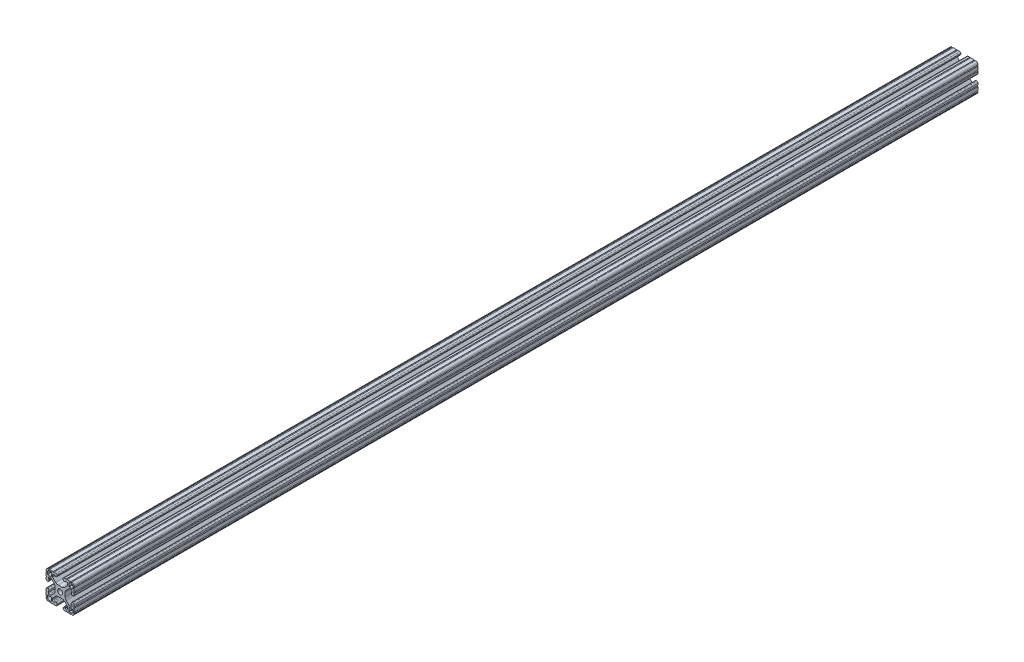
SolidWorks part; units mm, degrees
ref_plane "Front Plane" through (0, 0, 0) normal (0, 0, 1) x (1, 0, 0)
ref_plane "Top Plane" through (0, 0, 0) normal (0, 1, 0) x (1, 0, 0)
ref_plane "Right Plane" through (0, 0, 0) normal (1, 0, 0) x (0, 0, -1)
sketch "Sketch1" plane through (0, 0, 0) normal (0, 0, 1) x (1, 0, 0)
  line L0 (-10.0267, 12.1519) -> (-6.0215, 8.1473)
  line L1 (10.0267, -12.1519) -> (6.0215, -8.1473)
  line L2 (10.287, -14.5547) -> (10.287, -12.7802)
  line L3 (6.8141, -15.8247) -> (9.017, -15.8247)
  line L4 (-10.287, 14.5547) -> (-10.287, 12.7802)
  line L5 (6.8141, -14.986) -> (6.8141, -15.8247)
  line L6 (-6.8141, 15.8247) -> (-9.017, 15.8247)
  line L7 (2.6631, 6.7564) -> (-2.6631, 6.7564)
  line L8 (-6.8141, 14.986) -> (-6.8141, 15.8247)
  line L9 (-5.6388, 14.986) -> (-6.8141, 14.986)
  line L10 (-4.064, 17.4752) -> (-4.064, 16.5608)
  line L11 (-7.9756, 19.05) -> (-5.6388, 19.05)
  line L12 (-14.3256, 19.05) -> (-9.4996, 19.05)
  line L13 (-15.875, 19.05) -> (-15.8496, 19.05)
  line L14 (-19.05, 15.8496) -> (-19.05, 15.875)
  line L15 (-19.05, 9.4996) -> (-19.05, 14.3256)
  line L16 (-19.05, 5.6388) -> (-19.05, 7.9756)
  line L17 (5.6388, -14.986) -> (6.8141, -14.986)
  line L18 (4.064, -17.4752) -> (4.064, -16.5608)
  line L19 (7.9756, -19.05) -> (5.6388, -19.05)
  line L20 (-16.5608, 4.064) -> (-17.4752, 4.064)
  line L21 (14.3256, -19.05) -> (9.4996, -19.05)
  line L22 (-14.986, 6.7506) -> (-14.986, 5.6388)
  line L23 (-15.879, 6.7506) -> (-14.986, 6.7506)
  line L24 (15.875, -19.05) -> (15.8496, -19.05)
  line L25 (19.05, -15.8496) -> (19.05, -15.875)
  line L26 (-15.879, 8.9192) -> (-15.879, 6.7506)
  line L27 (-12.7428, 10.1892) -> (-14.609, 10.1892)
  line L28 (19.05, -9.4996) -> (19.05, -14.3256)
  line L29 (19.05, -5.6388) -> (19.05, -7.9756)
  line L30 (-8.1479, 5.9632) -> (-12.1142, 9.9289)
  line L31 (-16.891, 11.8618) -> (-12.2428, 11.8618)
  line L32 (-11.8618, 12.2428) -> (-11.8618, 16.891)
  line L33 (-12.2428, 17.272) -> (-14.478, 17.272)
  line L34 (-17.272, -14.478) -> (-17.272, -12.2428)
  line L35 (-12.2428, -17.272) -> (-14.478, -17.272)
  line L36 (-11.8618, -12.2428) -> (-11.8618, -16.891)
  line L37 (-16.891, -11.8618) -> (-12.2428, -11.8618)
  line L38 (-17.272, 14.478) -> (-17.272, 12.2428)
  line L39 (16.5608, -4.064) -> (17.4752, -4.064)
  line L40 (14.986, -6.7506) -> (14.986, -5.6388)
  line L41 (15.879, -6.7506) -> (14.986, -6.7506)
  line L42 (15.879, -8.9192) -> (15.879, -6.7506)
  line L43 (12.7428, -10.1892) -> (14.609, -10.1892)
  line L44 (8.1479, -5.9632) -> (12.1142, -9.9289)
  line L45 (6.7564, 2.6043) -> (6.7564, -2.6043)
  line L46 (17.272, 14.478) -> (17.272, 12.2428)
  line L47 (16.891, -11.8618) -> (12.2428, -11.8618)
  line L48 (11.8618, -12.2428) -> (11.8618, -16.891)
  line L49 (12.2428, -17.272) -> (14.478, -17.272)
  line L50 (17.272, -14.478) -> (17.272, -12.2428)
  line L51 (12.2428, 17.272) -> (14.478, 17.272)
  line L52 (11.8618, 12.2428) -> (11.8618, 16.891)
  line L53 (16.891, 11.8618) -> (12.2428, 11.8618)
  line L54 (8.1479, 5.9632) -> (12.1142, 9.9289)
  line L55 (12.7428, 10.1892) -> (14.609, 10.1892)
  line L56 (15.879, 8.9192) -> (15.879, 6.7506)
  line L57 (15.879, 6.7506) -> (14.986, 6.7506)
  line L58 (14.986, 6.7506) -> (14.986, 5.6388)
  line L59 (16.5608, 4.064) -> (17.4752, 4.064)
  line L60 (19.05, 5.6388) -> (19.05, 7.9756)
  line L61 (19.05, 9.4996) -> (19.05, 14.3256)
  line L62 (19.05, 15.8496) -> (19.05, 15.875)
  line L63 (15.875, 19.05) -> (15.8496, 19.05)
  line L64 (14.3256, 19.05) -> (9.4996, 19.05)
  line L65 (7.9756, 19.05) -> (5.6388, 19.05)
  line L66 (4.064, 17.4752) -> (4.064, 16.5608)
  line L67 (5.6388, 14.986) -> (6.8141, 14.986)
  line L68 (6.8141, 14.986) -> (6.8141, 15.8247)
  line L69 (6.8141, 15.8247) -> (9.017, 15.8247)
  line L70 (10.287, 14.5547) -> (10.287, 12.7802)
  line L71 (10.0267, 12.1519) -> (6.0215, 8.1473)
  line L72 (-6.7564, 2.6043) -> (-6.7564, -2.6043)
  line L73 (-8.1479, -5.9632) -> (-12.1142, -9.9289)
  line L74 (-12.7428, -10.1892) -> (-14.609, -10.1892)
  line L75 (-15.879, -8.9192) -> (-15.879, -6.7506)
  line L76 (-15.879, -6.7506) -> (-14.986, -6.7506)
  line L77 (-14.986, -6.7506) -> (-14.986, -5.6388)
  line L78 (-16.5608, -4.064) -> (-17.4752, -4.064)
  line L79 (-19.05, -5.6388) -> (-19.05, -7.9756)
  line L80 (-19.05, -9.4996) -> (-19.05, -14.3256)
  line L81 (-19.05, -15.8496) -> (-19.05, -15.875)
  line L82 (-15.875, -19.05) -> (-15.8496, -19.05)
  line L83 (-14.3256, -19.05) -> (-9.4996, -19.05)
  line L84 (-7.9756, -19.05) -> (-5.6388, -19.05)
  line L85 (-4.064, -17.4752) -> (-4.064, -16.5608)
  line L86 (-5.6388, -14.986) -> (-6.8141, -14.986)
  line L87 (-6.8141, -14.986) -> (-6.8141, -15.8247)
  line L88 (-6.8141, -15.8247) -> (-9.017, -15.8247)
  line L89 (-10.287, -14.5547) -> (-10.287, -12.7802)
  line L90 (-10.0267, -12.1519) -> (-6.0215, -8.1473)
  line L91 (-2.6631, -6.7564) -> (2.6631, -6.7564)
  arc A0 (-10.0267, 12.1519) -> (-10.287, 12.7802) centre (-9.3985, 12.7802) cw
  arc A1 (-19.05, -15.875) -> (-15.875, -19.05) centre (-15.875, -15.875) ccw construction
  arc A2 (-10.287, 14.5547) -> (-9.017, 15.8247) centre (-9.017, 14.5547) cw
  arc A3 (-4.064, 16.5608) -> (-5.6388, 14.986) centre (-5.6388, 16.5608) cw
  arc A4 (10.0267, -12.1519) -> (10.287, -12.7802) centre (9.3985, -12.7802) cw
  arc A5 (10.287, -14.5547) -> (9.017, -15.8247) centre (9.017, -14.5547) cw
  arc A6 (-5.6388, 19.05) -> (-4.064, 17.4752) centre (-5.6388, 17.4752) cw
  arc A7 (-7.9756, 19.05) -> (-9.4996, 19.05) centre (-8.7376, 19.05) cw
  arc A8 (-17.272, -14.478) -> (-14.478, -17.272) centre (-14.478, -14.478) ccw construction
  arc A9 (4.064, -16.5608) -> (5.6388, -14.986) centre (5.6388, -16.5608) cw
  arc A10 (-14.3256, 19.05) -> (-15.8496, 19.05) centre (-15.0876, 19.05) cw
  arc A11 (-19.05, 15.875) -> (-15.875, 19.05) centre (-15.875, 15.875) cw
  arc A12 (-6.0215, 8.1473) -> (-2.6631, 6.7564) centre (-2.6631, 11.5062) ccw
  arc A13 (6.0215, 8.1473) -> (2.6631, 6.7564) centre (2.6631, 11.5062) cw
  arc A14 (-19.05, 15.8496) -> (-19.05, 14.3256) centre (-19.05, 15.0876) cw
  arc A15 (-19.05, 9.4996) -> (-19.05, 7.9756) centre (-19.05, 8.7376) cw
  arc A16 (-17.4752, 4.064) -> (-19.05, 5.6388) centre (-17.4752, 5.6388) cw
  arc A17 (-14.986, 5.6388) -> (-16.5608, 4.064) centre (-16.5608, 5.6388) cw
  arc A18 (-15.879, 8.9192) -> (-14.609, 10.1892) centre (-14.609, 8.9192) cw
  arc A19 (-12.7428, 10.1892) -> (-12.1142, 9.9289) centre (-12.7428, 9.3002) cw
  arc A20 (-16.891, 11.8618) -> (-17.272, 12.2428) centre (-16.891, 12.2428) cw
  arc A21 (5.6388, -19.05) -> (4.064, -17.4752) centre (5.6388, -17.4752) cw
  arc A22 (7.9756, -19.05) -> (9.4996, -19.05) centre (8.7376, -19.05) cw
  arc A23 (14.3256, -19.05) -> (15.8496, -19.05) centre (15.0876, -19.05) cw
  arc A24 (-11.8618, 12.2428) -> (-12.2428, 11.8618) centre (-12.2428, 12.2428) cw
  arc A25 (19.05, -15.875) -> (15.875, -19.05) centre (15.875, -15.875) cw
  arc A26 (-12.2428, 17.272) -> (-11.8618, 16.891) centre (-12.2428, 16.891) cw
  arc A27 (-17.272, 14.478) -> (-14.478, 17.272) centre (-14.478, 14.478) cw
  arc A28 (19.05, -15.8496) -> (19.05, -14.3256) centre (19.05, -15.0876) cw
  arc A29 (19.05, -9.4996) -> (19.05, -7.9756) centre (19.05, -8.7376) cw
  arc A30 (17.4752, -4.064) -> (19.05, -5.6388) centre (17.4752, -5.6388) cw
  arc A31 (14.986, -5.6388) -> (16.5608, -4.064) centre (16.5608, -5.6388) cw
  arc A32 (15.879, -8.9192) -> (14.609, -10.1892) centre (14.609, -8.9192) cw
  arc A33 (12.7428, -10.1892) -> (12.1142, -9.9289) centre (12.7428, -9.3002) cw
  arc A34 (8.1479, -5.9632) -> (6.7564, -2.6043) centre (11.5062, -2.6043) cw
  arc A35 (6.7564, 2.6043) -> (8.1479, 5.9632) centre (11.5062, 2.6043) cw
  arc A36 (16.891, -11.8618) -> (17.272, -12.2428) centre (16.891, -12.2428) cw
  arc A37 (11.8618, -12.2428) -> (12.2428, -11.8618) centre (12.2428, -12.2428) cw
  arc A38 (-17.272, -14.478) -> (-14.478, -17.272) centre (-14.478, -14.478) ccw
  arc A39 (-12.2428, -17.272) -> (-11.8618, -16.891) centre (-12.2428, -16.891) ccw
  arc A40 (-11.8618, -12.2428) -> (-12.2428, -11.8618) centre (-12.2428, -12.2428) ccw
  arc A41 (-16.891, -11.8618) -> (-17.272, -12.2428) centre (-16.891, -12.2428) ccw
  arc A42 (12.2428, -17.272) -> (11.8618, -16.891) centre (12.2428, -16.891) cw
  circle A43 centre (0, 0) radius 3.3274
  arc A44 (17.272, -14.478) -> (14.478, -17.272) centre (14.478, -14.478) cw
  arc A45 (17.272, 14.478) -> (14.478, 17.272) centre (14.478, 14.478) ccw
  arc A46 (12.2428, 17.272) -> (11.8618, 16.891) centre (12.2428, 16.891) ccw
  arc A47 (11.8618, 12.2428) -> (12.2428, 11.8618) centre (12.2428, 12.2428) ccw
  arc A48 (16.891, 11.8618) -> (17.272, 12.2428) centre (16.891, 12.2428) ccw
  arc A49 (12.7428, 10.1892) -> (12.1142, 9.9289) centre (12.7428, 9.3002) ccw
  arc A50 (15.879, 8.9192) -> (14.609, 10.1892) centre (14.609, 8.9192) ccw
  arc A51 (14.986, 5.6388) -> (16.5608, 4.064) centre (16.5608, 5.6388) ccw
  arc A52 (17.4752, 4.064) -> (19.05, 5.6388) centre (17.4752, 5.6388) ccw
  arc A53 (19.05, 9.4996) -> (19.05, 7.9756) centre (19.05, 8.7376) ccw
  arc A54 (19.05, 15.8496) -> (19.05, 14.3256) centre (19.05, 15.0876) ccw
  arc A55 (19.05, 15.875) -> (15.875, 19.05) centre (15.875, 15.875) ccw
  arc A56 (14.3256, 19.05) -> (15.8496, 19.05) centre (15.0876, 19.05) ccw
  arc A57 (7.9756, 19.05) -> (9.4996, 19.05) centre (8.7376, 19.05) ccw
  arc A58 (5.6388, 19.05) -> (4.064, 17.4752) centre (5.6388, 17.4752) ccw
  arc A59 (4.064, 16.5608) -> (5.6388, 14.986) centre (5.6388, 16.5608) ccw
  arc A60 (10.287, 14.5547) -> (9.017, 15.8247) centre (9.017, 14.5547) ccw
  arc A61 (10.0267, 12.1519) -> (10.287, 12.7802) centre (9.3985, 12.7802) ccw
  arc A62 (-6.7564, 2.6043) -> (-8.1479, 5.9632) centre (-11.5062, 2.6043) ccw
  arc A63 (-8.1479, -5.9632) -> (-6.7564, -2.6043) centre (-11.5062, -2.6043) ccw
  arc A64 (-12.7428, -10.1892) -> (-12.1142, -9.9289) centre (-12.7428, -9.3002) ccw
  arc A65 (-15.879, -8.9192) -> (-14.609, -10.1892) centre (-14.609, -8.9192) ccw
  arc A66 (-14.986, -5.6388) -> (-16.5608, -4.064) centre (-16.5608, -5.6388) ccw
  arc A67 (-17.4752, -4.064) -> (-19.05, -5.6388) centre (-17.4752, -5.6388) ccw
  arc A68 (-19.05, -9.4996) -> (-19.05, -7.9756) centre (-19.05, -8.7376) ccw
  arc A69 (-19.05, -15.8496) -> (-19.05, -14.3256) centre (-19.05, -15.0876) ccw
  arc A70 (-19.05, -15.875) -> (-15.875, -19.05) centre (-15.875, -15.875) ccw
  arc A71 (-14.3256, -19.05) -> (-15.8496, -19.05) centre (-15.0876, -19.05) ccw
  arc A72 (-7.9756, -19.05) -> (-9.4996, -19.05) centre (-8.7376, -19.05) ccw
  arc A73 (-5.6388, -19.05) -> (-4.064, -17.4752) centre (-5.6388, -17.4752) ccw
  arc A74 (-4.064, -16.5608) -> (-5.6388, -14.986) centre (-5.6388, -16.5608) ccw
  arc A75 (-10.287, -14.5547) -> (-9.017, -15.8247) centre (-9.017, -14.5547) ccw
  arc A76 (-10.0267, -12.1519) -> (-10.287, -12.7802) centre (-9.3985, -12.7802) ccw
  arc A77 (-2.6631, -6.7564) -> (-6.0215, -8.1473) centre (-2.6631, -11.5062) ccw
  arc A78 (6.0215, -8.1473) -> (2.6631, -6.7564) centre (2.6631, -11.5062) ccw
  point P134 (0, 0)
extrude "Boss-Extrude1" add sketch "Sketch1" along normal mid plane 1219.2
